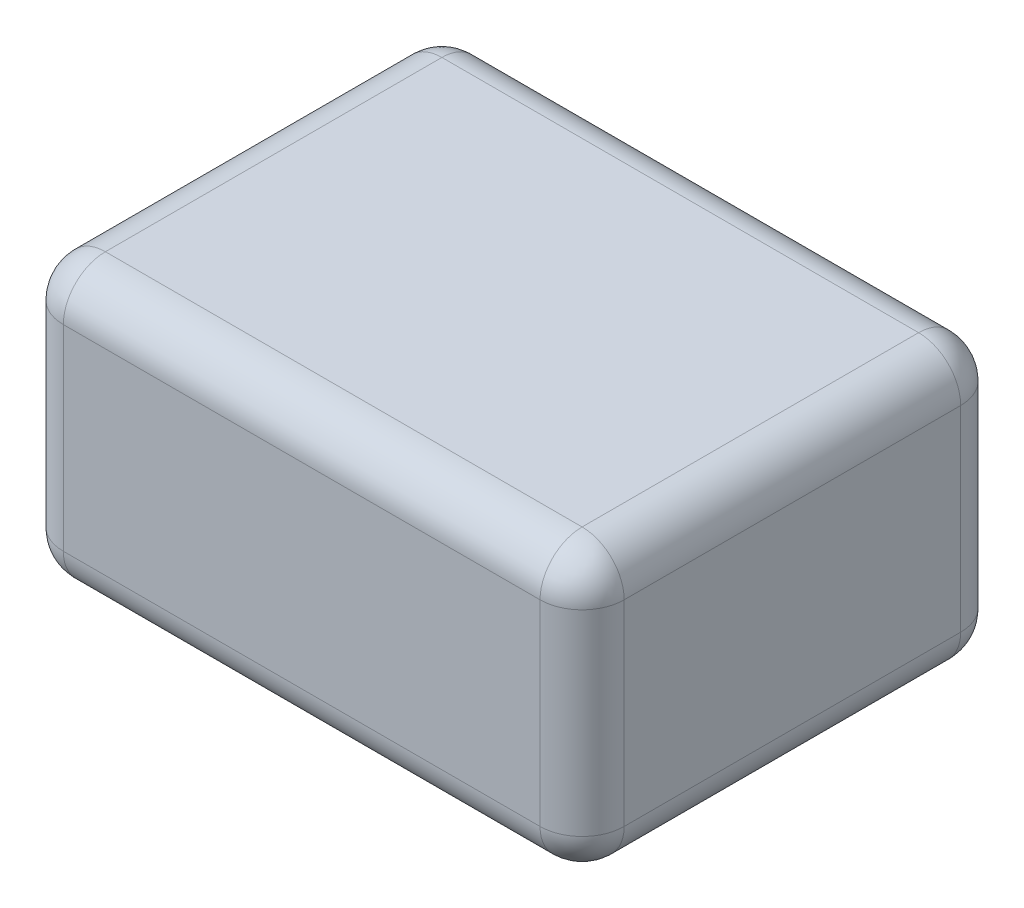
SolidWorks part; units mm, degrees
ref_plane "Front Plane" through (0, 0, 0) normal (0, 0, 1) x (1, 0, 0)
ref_plane "Top Plane" through (0, 0, 0) normal (0, 1, 0) x (1, 0, 0)
ref_plane "Right Plane" through (0, 0, 0) normal (1, 0, 0) x (0, 0, -1)
sketch "Sketch1" plane through (0, 0, 0) normal (0, 1, 0) x (1, 0, 0)
  line L0 (-20, -15) -> (20, -15)
  line L1 (20, -15) -> (20, 15)
  line L2 (20, 15) -> (-20, 15)
  line L3 (-20, 15) -> (-20, -15)
extrude "Boss-Extrude1" add sketch "Sketch1" along normal blind 20
fillet "Fillet1" radius 3 12 edges at (-20, 0, 0) (0, 0, 15) (20, 0, 0) (0, 0, -15) (-20, 20, 0) (0, 20, 15) (20, 20, 0) (0, 20, -15) (-20, 10, -15) (20, 10, -15) (20, 10, 15) (-20, 10, 15)
